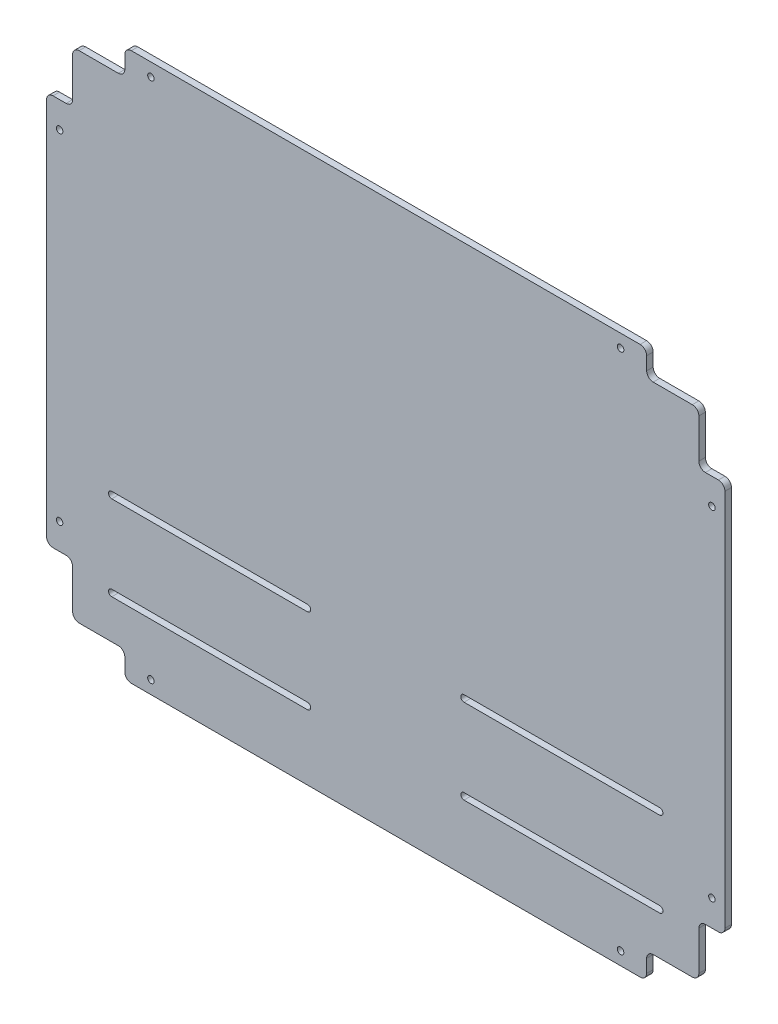
SolidWorks part; units mm, degrees
material "环氧树脂,未充填"
ref_plane "前视基准面" through (0, 0, 0) normal (0, 0, 1) x (1, 0, 0)
ref_plane "上视基准面" through (0, 0, 0) normal (0, 1, 0) x (1, 0, 0)
ref_plane "右视基准面" through (0, 0, 0) normal (1, 0, 0) x (0, 0, -1)
sketch "草图1" plane through (0, 0, 0) normal (0, 0, 1) x (1, 0, 0)
  line L6 (-260, 210) -> (260, 210)
  line L10 (-260, 210) -> (-260, -210)
  line L11 (-260, -210) -> (260, -210)
  line L12 (260, 210) -> (260, -210)
  line L13 (-260, 210) -> (260, -210) construction
  line L14 (-260, -210) -> (260, 210) construction
  point P0 (0, 0)
  point P1 (0, 0)
  dimension "D1" = 520
  dimension "D2" = 420
extrude "凸台-拉伸2" add sketch "草图1" along normal blind 5
sketch "草图2" plane through (0, 0, 0) normal (0, 0, -1) x (-1, 0, 0)
  line L0 (240, -190) -> (240, -150)
  line L1 (240, 190) -> (200, 190)
  line L2 (-240, 190) -> (-240, 150)
  line L3 (-240, -190) -> (-200, -190)
  line L4 (-260, 210) -> (-260, -210)
  line L5 (-260, -210) -> (260, -210)
  line L6 (260, -210) -> (260, 210)
  line L7 (260, 210) -> (-260, 210)
  line L8 (-260, 210) -> (-260, 150)
  line L9 (-260, -210) -> (-200, -210)
  line L10 (260, -210) -> (260, -150)
  line L11 (260, 210) -> (200, 210)
  line L12 (260, -150) -> (240, -150)
  line L13 (200, -190) -> (200, -210)
  line L14 (-240, -150) -> (-260, -150)
  line L15 (-200, -190) -> (-200, -210)
  line L16 (260, 150) -> (240, 150)
  line L17 (200, 210) -> (200, 190)
  line L18 (-200, 210) -> (-200, 190)
  line L19 (-240, 150) -> (-260, 150)
  line L20 (260, 150) -> (260, 210)
  line L21 (260, -210) -> (260, 210) construction
  line L22 (240, 150) -> (240, 190)
  line L23 (240, -190) -> (240, 190) construction
  line L24 (-240, -150) -> (-240, -190)
  line L25 (-240, 190) -> (-240, -190) construction
  line L26 (-260, -150) -> (-260, -210)
  line L27 (-260, 210) -> (-260, -210) construction
  line L28 (200, -210) -> (260, -210)
  line L29 (-260, -210) -> (260, -210) construction
  line L30 (200, -190) -> (240, -190)
  line L31 (-240, -190) -> (240, -190) construction
  line L32 (-200, 190) -> (-240, 190)
  line L33 (240, 190) -> (-240, 190) construction
  line L34 (-200, 210) -> (-260, 210)
  line L35 (260, 210) -> (-260, 210) construction
  line L36 (260, 210) -> (260, -210) construction
  line L37 (260, -210) -> (-260, -210) construction
  line L38 (-260, 210) -> (260, 210) construction
  line L39 (-260, -210) -> (-260, 210) construction
  circle A0 centre (-180, 200) radius 2.5
  circle A1 centre (-250, 130) radius 2.5
  circle A2 centre (-250, -130) radius 2.5
  circle A3 centre (-180, -200) radius 2.5
  circle A4 centre (180, -200) radius 2.5
  circle A5 centre (250, -130) radius 2.5
  circle A6 centre (250, 130) radius 2.5
  circle A7 centre (180, 200) radius 2.5
  dimension "D8" = 5
  dimension "D9" = 10
  dimension "D10" = 20
  dimension "D11" = 5
  dimension "D12" = 10
  dimension "D14" = 5
  dimension "D17" = 5
  dimension "D18" = 20
  dimension "D20" = 5
  dimension "D21" = 10
  dimension "D22" = 20
  dimension "D23" = 5
  dimension "D24" = 10
  dimension "D25" = 20
  dimension "D26" = 5
  dimension "D27" = 20
  dimension "D28" = 10
  dimension "D29" = 5
  dimension "D30" = 10
  dimension "D31" = 20
  dimension "D3" = 60
  dimension "D4" = 60
  dimension "D5" = 60
  dimension "D6" = 60
  dimension "D7" = 60
  dimension "D13" = 20
  dimension "D15" = 20
  dimension "D16" = 10
  dimension "D19" = 10
  dimension "D1" = 0
  dimension "D2" = 20
extrude "切除-拉伸1" cut sketch "草图2" against normal through all
fillet "圆角1" radius 5 20 edges at (200, -210, 2.5) (200, -190, 2.5) (240, -190, 2.5) (240, -150, 2.5) (260, -150, 2.5) (260, 150, 2.5) (240, 150, 2.5) (240, 190, 2.5) (200, 190, 2.5) (200, 210, 2.5) (-200, 210, 2.5) (-200, 190, 2.5) (-240, 190, 2.5) (-240, 150, 2.5) (-260, 150, 2.5) (-260, -150, 2.5) (-240, -150, 2.5) (-240, -190, 2.5) (-200, -190, 2.5) (-200, -210, 2.5)
sketch "草图3" plane through (0, 0, 5) normal (0, 0, 1) x (1, 0, 0)
  line L2 (-210, -95) -> (-60, -95)
  line L3 (-210, -90) -> (-60, -90)
  line L7 (260, -145) -> (260, 145) construction
  line L8 (-195, -210) -> (195, -210) construction
  line L9 (-210, -160) -> (-60, -160)
  line L10 (-210, -155) -> (-60, -155)
  line L11 (-235, -190) -> (-205, -190) construction
  line L12 (-240, -155) -> (-240, -185) construction
  line L13 (240, -185) -> (240, -155) construction
  line L16 (60, -160) -> (210, -160)
  line L17 (60, -155) -> (210, -155)
  line L18 (60, -95) -> (210, -95)
  line L19 (60, -90) -> (210, -90)
  arc A4 (-210, -155) -> (-210, -160) centre (-210, -157.5) ccw
  arc A5 (210, -155) -> (210, -160) centre (210, -157.5) cw
  arc A6 (-210, -90) -> (-210, -95) centre (-210, -92.5) ccw
  arc A7 (210, -90) -> (210, -95) centre (210, -92.5) cw
  arc A8 (60, -160) -> (60, -155) centre (60, -157.5) cw
  arc A9 (60, -90) -> (60, -95) centre (60, -92.5) ccw
  arc A10 (-60, -160) -> (-60, -155) centre (-60, -157.5) ccw
  arc A11 (-60, -95) -> (-60, -90) centre (-60, -92.5) ccw
  dimension "D3" = 30
  dimension "D1" = 5
  dimension "D2" = 30
  dimension "D4" = 30
  dimension "D6" = 60
  dimension "D7" = 150
  dimension "D8" = 150
  dimension "D9" = 150
  dimension "D10" = 150
  dimension "D5" = 2
extrude "切除-拉伸2" cut sketch "草图3" against normal blind 10
